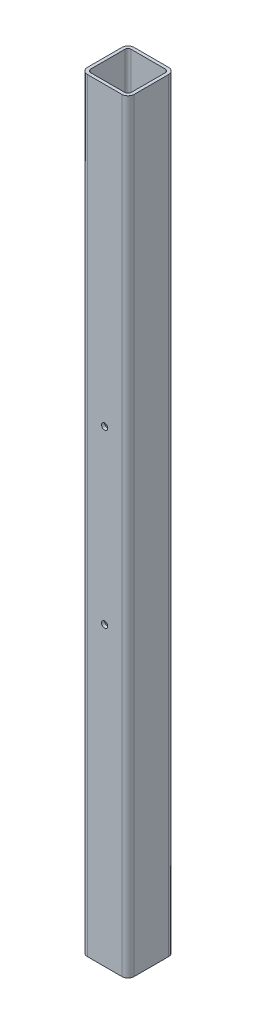
SolidWorks part; units mm, degrees
material "AISI 1010 钢，热轧条材"
ref_plane "前视基准面" through (0, 0, 0) normal (0, 0, 1) x (1, 0, 0)
ref_plane "上视基准面" through (0, 0, 0) normal (0, 1, 0) x (1, 0, 0)
ref_plane "右视基准面" through (0, 0, 0) normal (1, 0, 0) x (0, 0, -1)
sketch "草图1" plane through (0, 0, 0) normal (0, 1, 0) x (1, 0, 0)
  line L0 (-11, -13) -> (11, -13)
  line L1 (-11, -15) -> (11, -15)
  line L2 (-15, -11) -> (-15, 11)
  line L3 (-11, 15) -> (11, 15)
  line L4 (15, -11) -> (15, 11)
  line L5 (13, -11) -> (13, 11)
  line L6 (-11, 13) -> (11, 13)
  line L7 (-13, -11) -> (-13, 11)
  arc A0 (-11, -15) -> (-15, -11) centre (-11, -11) cw
  arc A1 (11, -15) -> (15, -11) centre (11, -11) ccw
  arc A2 (11, 15) -> (15, 11) centre (11, 11) cw
  arc A3 (-15, 11) -> (-11, 15) centre (-11, 11) cw
  arc A4 (11, -13) -> (13, -11) centre (11, -11) ccw
  arc A5 (11, 13) -> (13, 11) centre (11, 11) cw
  arc A6 (-13, 11) -> (-11, 13) centre (-11, 11) cw
  arc A7 (-11, -13) -> (-13, -11) centre (-11, -11) cw
extrude "凸台-拉伸1" add sketch "草图1" along normal mid plane 490
sketch "草图3" plane through (0, 0, 0) normal (1, 0, 0) x (0, 0, -1)
  line L0 (-15, 151.366) -> (-15, 197.4264) construction
  line L1 (-15, 245) -> (-15, -245) construction
  line L2 (-15, 197.4264) -> (15, 227.4264) construction
  line L3 (15, 227.4264) -> (15, 245) construction
  line L4 (15, 245) -> (45, 245) construction
  line L5 (45, 245) -> (45, 215) construction
  line L6 (45, 215) -> (15, 185) construction
  line L7 (15, 185) -> (15, 151.366) construction
  line L8 (15, 245) -> (15, -245) construction
  line L9 (15, 151.366) -> (-15, 151.366) construction
  line L10 (-15, 0) -> (15, 0) construction
  line L11 (-15, 245) -> (-15, -245) construction
  line L12 (15, 245) -> (15, -245) construction
  line L13 (15, -151.366) -> (-15, -151.366) construction
  line L14 (15, -185) -> (15, -151.366) construction
  line L15 (45, -215) -> (15, -185) construction
  line L16 (45, -245) -> (45, -215) construction
  line L17 (15, -245) -> (45, -245) construction
  line L18 (15, -227.4264) -> (15, -245) construction
  line L19 (-15, -197.4264) -> (15, -227.4264) construction
  line L20 (-15, -151.366) -> (-15, -197.4264) construction
  line L21 (15, 227.4264) -> (45, 215) construction
  line L22 (15, 185) -> (-15, 197.4264) construction
  line L23 (30, 245) -> (30, 221.2132)
  line L24 (30, 221.2132) -> (0, 191.2132)
  line L25 (0, 191.2132) -> (0, 0)
  dimension "D1" = 30
  dimension "D2" = 30
  dimension "D3" = 45
  dimension "D4" = 490
  dimension "D5" = 30
sketch "草图2" plane through (0, 0, 0) normal (0, 0, 1) x (1, 0, 0)
  line L0 (15, 0) -> (-15, 0) construction
  line L1 (15, 245) -> (15, -245) construction
  line L2 (-15, 245) -> (-15, -245) construction
  circle A0 centre (0, 55) radius 2
  circle A1 centre (0, -55) radius 2
  dimension "D2" = 4
  dimension "D1" = 110
extrude "切除-拉伸1" cut sketch "草图2" against normal through all both and the other way through all
